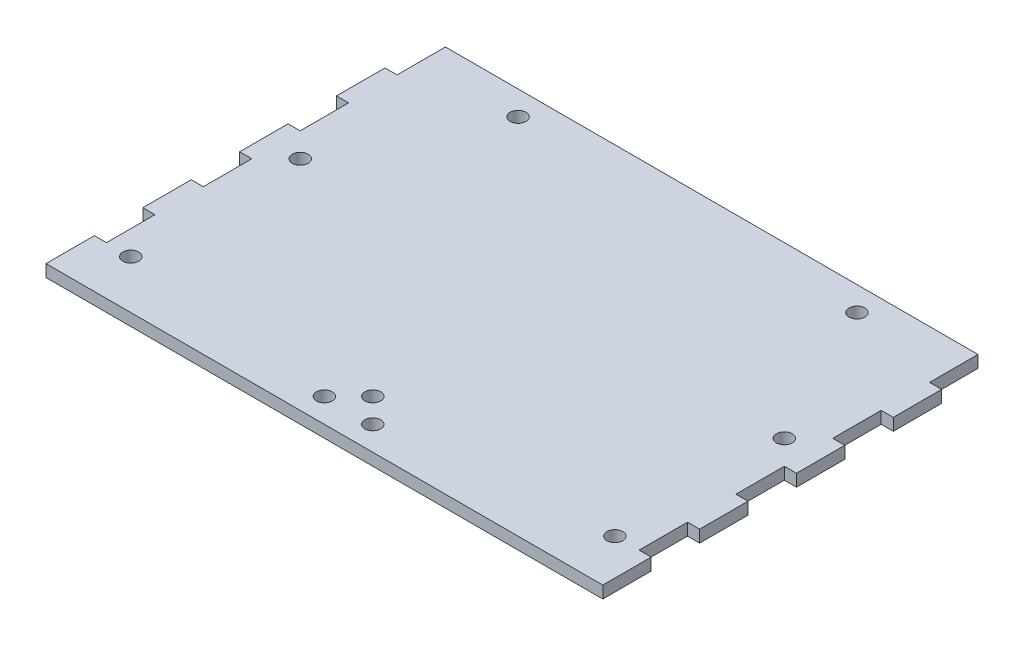
SolidWorks part; units mm, degrees
ref_plane "Front Plane" through (0, 0, 0) normal (0, 0, 1) x (1, 0, 0)
ref_plane "Top Plane" through (0, 0, 0) normal (0, 1, 0) x (1, 0, 0)
ref_plane "Right Plane" through (0, 0, 0) normal (1, 0, 0) x (0, 0, -1)
sketch "Sketch2" plane through (0, 0, 0) normal (0, 1, 0) x (1, 0, 0)
  line L0 (3.175, 13.2292) -> (3.175, 25.9292)
  line L1 (3.175, 13.2292) -> (0, 13.2292)
  line L2 (0, 13.2292) -> (0, 0.5292)
  line L3 (3.175, 25.9292) -> (0, 25.9292)
  line L4 (0, 38.6292) -> (0, 25.9292)
  line L5 (0, 38.6292) -> (3.175, 38.6292)
  line L6 (3.175, 51.3292) -> (0, 51.3292)
  line L7 (0, 64.0292) -> (0, 51.3292)
  line L8 (0, 64.0292) -> (3.175, 64.0292)
  line L9 (3.175, 76.7292) -> (0, 76.7292)
  line L10 (3.175, 38.6292) -> (3.175, 51.3292)
  line L12 (0, 89.4292) -> (3.175, 89.4292)
  line L13 (3.175, 51.3292) -> (142.875, 51.3292) construction
  line L14 (3.175, 64.0292) -> (3.175, 76.7292)
  line L15 (142.875, 89.4292) -> (117.475, 89.4292) construction
  line L16 (117.475, 89.4292) -> (117.475, 95.7792) construction
  line L17 (73.025, 0.5292) -> (73.025, 13.2292) construction
  line L18 (3.175, 89.4292) -> (3.175, 102.1292)
  line L19 (73.025, 6.8792) -> (79.375, 6.8792) construction
  line L20 (73.025, 6.8792) -> (66.675, 6.8792) construction
  line L21 (0, 0.5292) -> (146.05, 0.5292)
  line L22 (28.575, 89.4292) -> (28.575, 95.7792) construction
  line L23 (73.025, 0.5292) -> (73.025, 102.1292) construction
  line L24 (0, 89.4292) -> (0, 76.7292)
  line L25 (146.05, 89.4292) -> (146.05, 76.7292)
  line L26 (3.175, 89.4292) -> (28.575, 89.4292) construction
  line L27 (3.175, 13.2292) -> (9.525, 13.2292) construction
  line L28 (146.05, 64.0292) -> (146.05, 51.3292)
  line L29 (3.175, 102.1292) -> (142.875, 102.1292)
  line L30 (142.875, 51.3292) -> (146.05, 51.3292)
  line L31 (142.875, 89.4292) -> (142.875, 102.1292)
  line L32 (146.05, 38.6292) -> (146.05, 25.9292)
  line L35 (142.875, 64.0292) -> (142.875, 76.7292)
  line L37 (146.05, 89.4292) -> (142.875, 89.4292)
  line L39 (142.875, 38.6292) -> (142.875, 51.3292)
  line L40 (142.875, 76.7292) -> (146.05, 76.7292)
  line L41 (146.05, 64.0292) -> (142.875, 64.0292)
  line L44 (146.05, 38.6292) -> (142.875, 38.6292)
  line L46 (142.875, 25.9292) -> (146.05, 25.9292)
  line L47 (146.05, 13.2292) -> (146.05, 0.5292)
  line L48 (142.875, 13.2292) -> (146.05, 13.2292)
  line L51 (142.875, 13.2292) -> (142.875, 25.9292)
  circle A0 centre (136.525, 57.6792) radius 2.0828
  circle A1 centre (9.525, 13.2292) radius 2.0828
  circle A2 centre (9.525, 57.6792) radius 2.0828
  circle A3 centre (136.525, 13.2292) radius 2.0828
  circle A4 centre (79.375, 6.8792) radius 2.0828
  circle A5 centre (73.025, 13.2292) radius 2.0828
  circle A6 centre (66.675, 6.8792) radius 2.0828
  circle A7 centre (117.475, 95.7792) radius 2.0828
  circle A8 centre (28.575, 95.7792) radius 2.0828
  dimension "D1" = 6.35
  dimension "D3" = 25.4
  dimension "D2" = 25.4
  dimension "D4" = 6.35
  dimension "D5" = 6.35
  dimension "D6" = 6.35
extrude "Boss-Extrude1" add sketch "Sketch2" along normal blind 3.175
